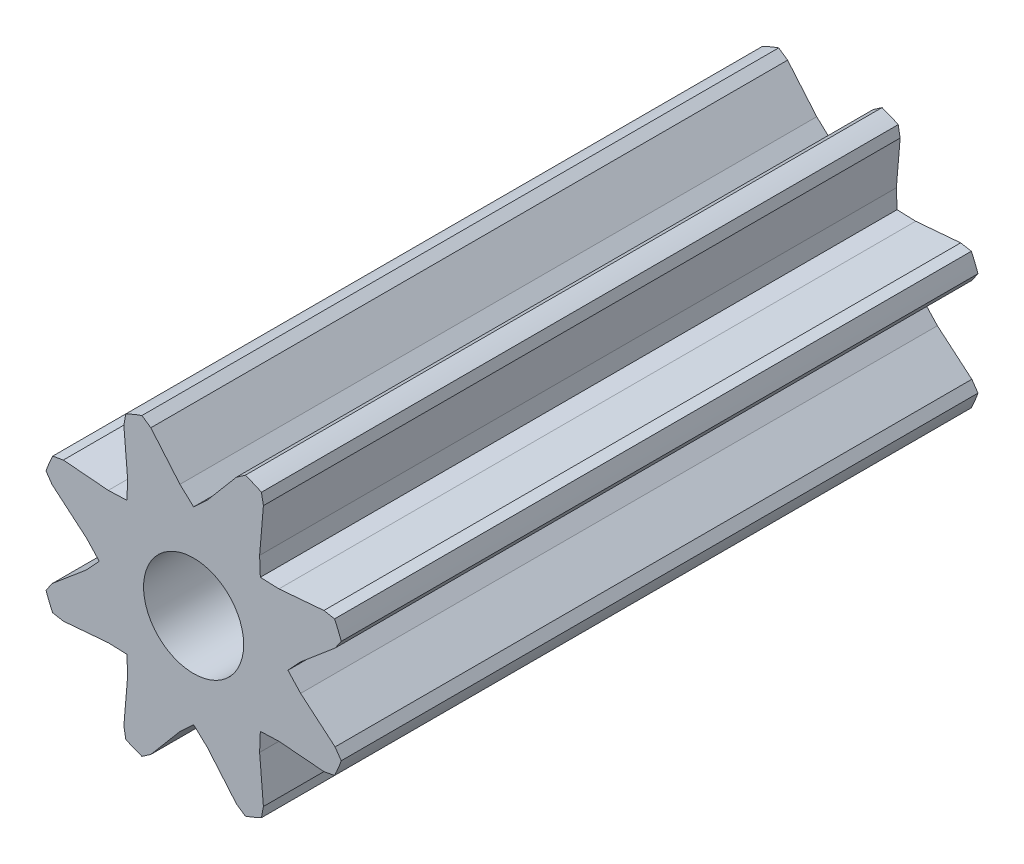
SolidWorks part; units mm, degrees
ref_plane "Front Plane" through (0, 0, 0) normal (0, 0, 1) x (1, 0, 0)
ref_plane "Top Plane" through (0, 0, 0) normal (0, 1, 0) x (1, 0, 0)
ref_plane "Right Plane" through (0, 0, 0) normal (1, 0, 0) x (0, 0, -1)
sketch "Sketch1" plane through (0, 0, 0) normal (0, 0, 1) x (1, 0, 0)
  line L1 (1.2374, -1.2374) -> (-1.2374, -1.2374) construction
  line L2 (1.2374, -1.2374) -> (1.2374, 1.2374) construction
  line L3 (1.2374, 1.2374) -> (-1.2374, 1.2374) construction
  line L4 (-1.2374, -1.2374) -> (-1.2374, 1.2374) construction
  line L5 (1.2374, -1.2374) -> (-1.2374, 1.2374) construction
  line L6 (1.2374, 1.2374) -> (-1.2374, -1.2374) construction
  circle A0 centre (0, 0) radius 5
  circle A1 centre (0, 0) radius 1.75 construction
  dimension "D1" = 10
  dimension "D2" = 3.5
extrude "Boss-Extrude1" add sketch "Sketch1" along normal blind 20.355
sketch "Sketch2" plane through (0, 0, 0) normal (0, 0, 1) x (1, 0, 0)
  line L0 (0, 0) -> (0, 8.8612) construction
  line L1 (0, 3.0153) -> (-0.4371, 3.4206)
  line L8 (-1.8991, 5.2712) -> (0, 6.2652)
  line L11 (-0.4371, 3.4206) -> (-1.3679, 4.5219)
  line L12 (-1.3679, 4.5219) -> (-1.6525, 4.719)
  line L13 (-1.6525, 4.719) -> (-1.8991, 5.2712)
  line L14 (1.6525, 4.719) -> (1.8991, 5.2712)
  line L15 (1.3679, 4.5219) -> (1.6525, 4.719)
  line L16 (0.4371, 3.4206) -> (1.3679, 4.5219)
  line L17 (1.8991, 5.2712) -> (0, 6.2652)
  line L18 (0, 3.0153) -> (0.4371, 3.4206)
  circle A14 centre (0, 0) radius 5 construction
  point P4 (-1.5564, 3.8849)
  point P16 (0, 5)
  point P17 (-0.604, 3.0153)
  point P18 (0, 2.3389)
  point P19 (0, 8.8612)
  point P20 (-1.8661, 3.6697)
  point P21 (-2.0191, 4.5742)
  point P22 (-1.0532, 4.0106)
  point P23 (0, 3.0153)
  point P24 (-0.4371, 3.4206)
  point P25 (-1.6525, 4.719)
  point P26 (-1.3679, 4.5219)
  point P27 (0, 6.2652)
  point P28 (-1.3216, 4.8222)
  point P29 (-1.8991, 5.2712)
extrude "Cut-Extrude1" cut sketch "Sketch2" along normal through all
pattern_circular "CirPattern1" count 8 over 360 about axis through (0, 0, 0) along (0, 0, 1) of "Cut-Extrude1"
sketch "Sketch3" plane through (0, 0, 0) normal (0, 0, 1) x (1, 0, 0)
  circle A0 centre (0, 0) radius 7.5
  dimension "D1" = 15
sketch "Sketch4" plane through (0, 0, 20.355) normal (0, 0, 1) x (1, 0, 0)
  circle A0 centre (0, 0) radius 1.6
  dimension "D1" = 3.2
extrude "Cut-Extrude2" cut sketch "Sketch4" against normal through all both and the other way through all
equation "\"circle\"=10"
equation "\"D1@Sketch1\"=\"circle\""
